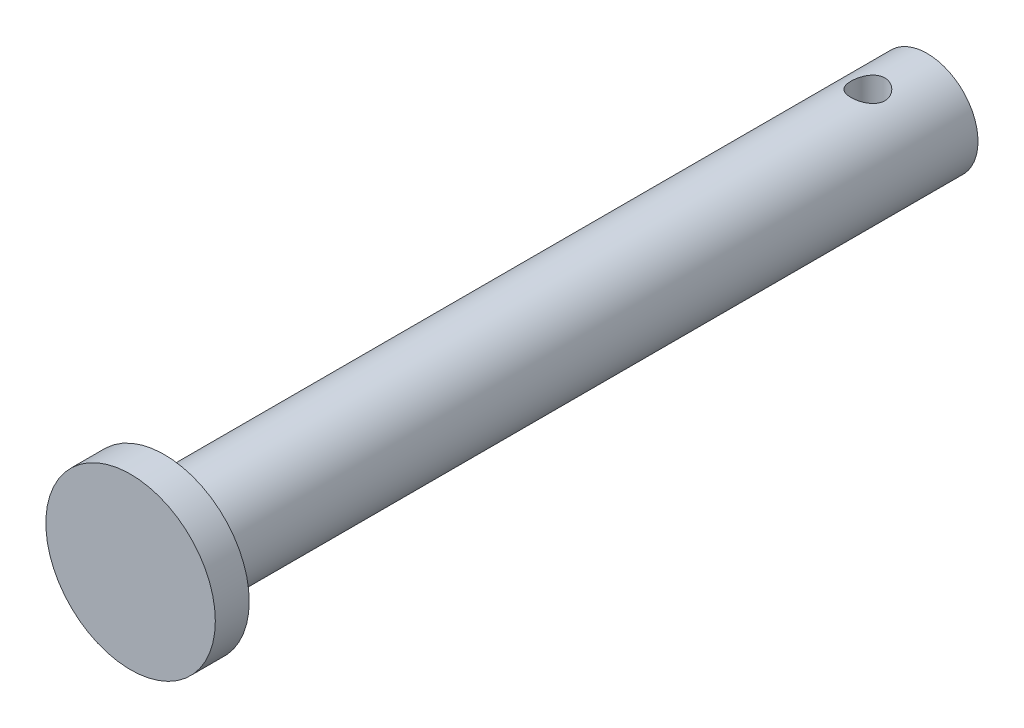
SolidWorks part; units mm, degrees
ref_plane "Front Plane" through (0, 0, 0) normal (0, 0, 1) x (1, 0, 0)
ref_plane "Top Plane" through (0, 0, 0) normal (0, 1, 0) x (1, 0, 0)
ref_plane "Right Plane" through (0, 0, 0) normal (1, 0, 0) x (0, 0, -1)
sketch "Sketch1" plane through (0, 0, 0) normal (0, 0, 1) x (1, 0, 0)
  circle A0 centre (0, 0) radius 3
  dimension "D1" = 6
extrude "Boss-Extrude1" add sketch "Sketch1" along normal blind 45
sketch "Sketch2" plane through (0, 0, 45) normal (0, 0, 1) x (1, 0, 0)
  circle A2 centre (0, 0) radius 5
  circle A3 centre (0, 0) radius 5
  dimension "D1" = 2
extrude "Boss-Extrude2" add sketch "Sketch2" along normal blind 2
sketch "Sketch3" plane through (0, 0, 0) normal (0, 1, 0) x (1, 0, 0)
  line L0 (3, -45) -> (3, 0) construction
  line L1 (3, 0) -> (-3, 0) construction
  circle A0 centre (0, -3.5) radius 1
  dimension "D1" = 2
  dimension "D2" = 3
  dimension "D3" = 3.5
extrude "Cut-Extrude1" cut sketch "Sketch3" against normal through all both and the other way through all
sketch "Sketch4" plane through (0, 0, 0) normal (0, 0, -1) x (-1, 0, 0)
  circle A2 centre (0, 0) radius 1.5
  circle A3 centre (0, 0) radius 1.5
  dimension "D1" = 1.5
extrude "Cut-Extrude2" cut sketch "Sketch4" against normal up to surface (45 mm away) up to face at (3, 0, 45)
